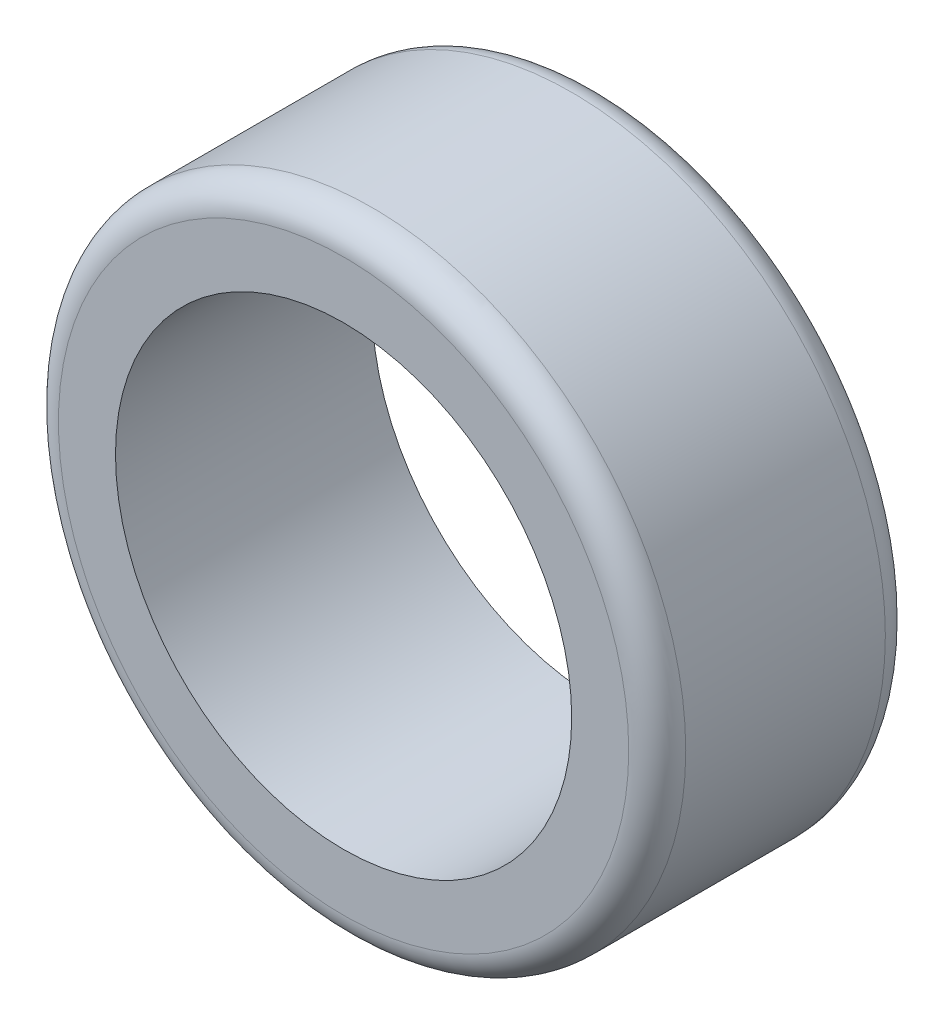
SolidWorks part; units mm, degrees
ref_plane "Front Plane" through (0, 0, 0) normal (0, 0, 1) x (1, 0, 0)
ref_plane "Top Plane" through (0, 0, 0) normal (0, 1, 0) x (1, 0, 0)
ref_plane "Right Plane" through (0, 0, 0) normal (1, 0, 0) x (0, 0, -1)
sketch "Sketch1" plane through (0, 0, 0) normal (0, 0, 1) x (1, 0, 0)
  circle A0 centre (0, 0) radius 11
  circle A1 centre (0, 0) radius 8
  dimension "D1" = 22
  dimension "D2" = 16
extrude "Boss-Extrude1" add sketch "Sketch1" along normal blind 9
fillet "Fillet1" radius 1 2 edges at (11, 0, 0) (11, 0, 9)
